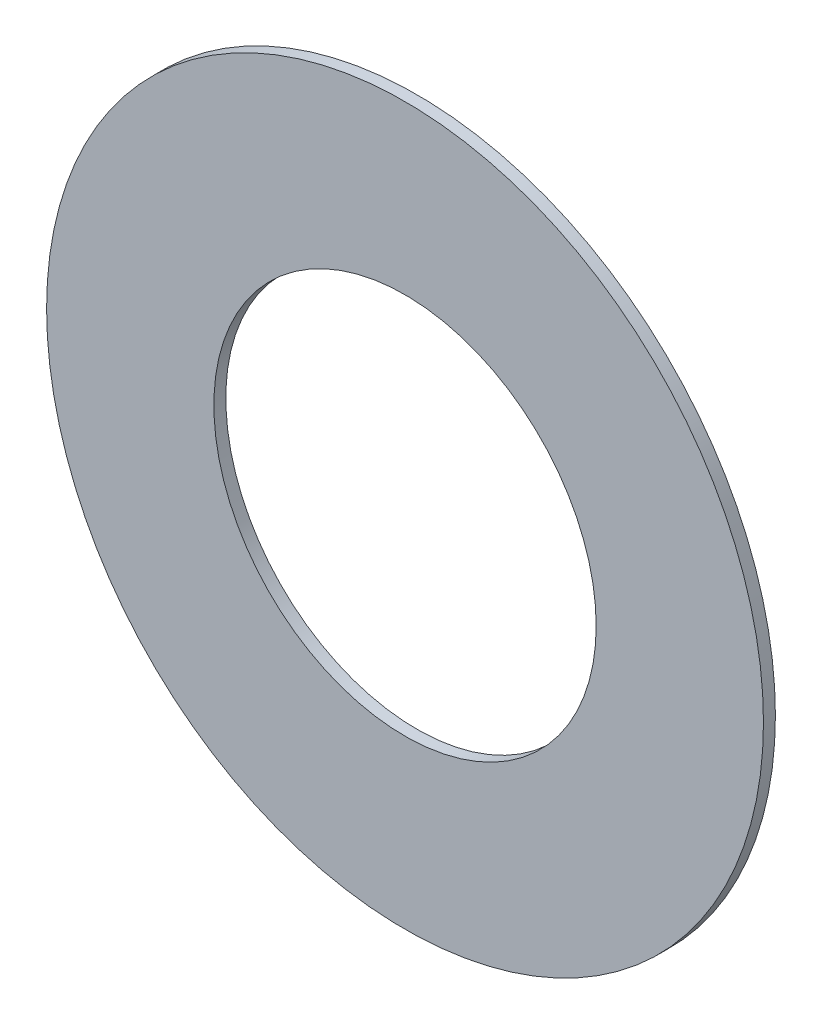
SolidWorks part; units mm, degrees
ref_plane "前视基准面" through (0, 0, 0) normal (0, 0, 1) x (1, 0, 0)
ref_plane "上视基准面" through (0, 0, 0) normal (0, 1, 0) x (1, 0, 0)
ref_plane "右视基准面" through (0, 0, 0) normal (1, 0, 0) x (0, 0, -1)
sketch "草图1" plane through (0, 0, 0) normal (0, 0, 1) x (1, 0, 0)
  circle A0 centre (-71.4447, 26.318) radius 60
  dimension "D1" = 120
extrude "凸台-拉伸1" add sketch "草图1" along normal blind 2
shell "抽壳5" thickness 28
